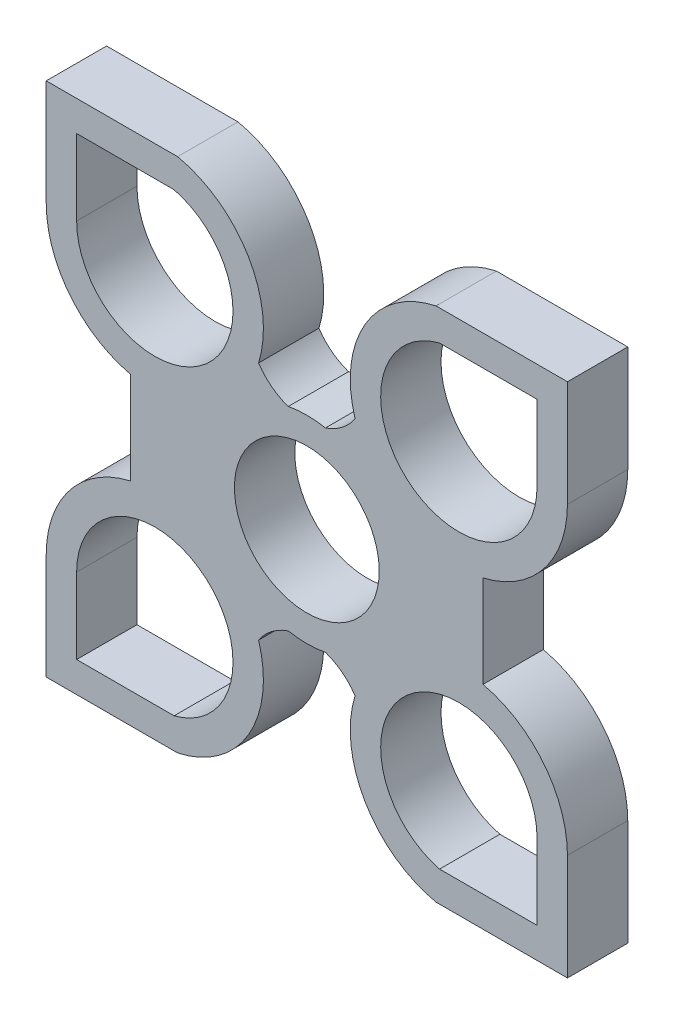
SolidWorks part; units mm, degrees
ref_plane "Front Plane" through (0, 0, 0) normal (0, 0, 1) x (1, 0, 0)
ref_plane "Top Plane" through (0, 0, 0) normal (0, 1, 0) x (1, 0, 0)
ref_plane "Right Plane" through (0, 0, 0) normal (1, 0, 0) x (0, 0, -1)
sketch "Sketch1" plane through (0, 0, 0) normal (0, 0, 1) x (1, 0, 0)
  line L1 (108, 63) -> (108, 107)
  line L2 (108, 107) -> (53.566, 107)
  line L3 (0, 107) -> (0, 0) construction
  line L4 (-95.4, -94.4) -> (-55.0125, -94.4)
  line L6 (0, 0) -> (73, 0) construction
  line L7 (73, -19.1252) -> (73, 19.1252)
  line L8 (-108, 107) -> (-53.566, 107)
  line L9 (95.4, 94.4) -> (55.0125, 94.4)
  line L10 (95.4, 63) -> (95.4, 94.4)
  line L11 (-95.4, 63) -> (-95.4, 94.4)
  line L12 (-95.4, 94.4) -> (-55.0125, 94.4)
  line L13 (-108, 63) -> (-108, 107)
  line L14 (-95.4, -63) -> (-95.4, -94.4)
  line L15 (-108, -107) -> (-53.566, -107)
  line L16 (-108, -63) -> (-108, -107)
  line L17 (95.4, -63) -> (95.4, -94.4)
  line L18 (95.4, -94.4) -> (55.0125, -94.4)
  line L19 (108, -107) -> (53.566, -107)
  line L20 (108, -63) -> (108, -107)
  line L21 (-73, -19.1252) -> (-73, 19.1252)
  circle A0 centre (0, 0) radius 30
  circle A1 centre (0, 0) radius 41
  arc A2 (53.566, 107) -> (108, 63) centre (63, 63) ccw
  arc A3 (30.5, 63) -> (95.4, 65.5475) centre (63, 63) ccw
  arc A5 (7.7032, 40.2698) -> (20, 49.7335) centre (0, 63) ccw
  arc A6 (55.0125, 94.4) -> (95.4, 63) centre (63, 63) ccw
  arc A7 (-7.7032, 40.2698) -> (-20, 49.7335) centre (0, 63) cw
  arc A8 (-53.566, 107) -> (-108, 63) centre (-63, 63) cw
  arc A9 (-30.5, 63) -> (-95.4, 65.5475) centre (-63, 63) cw
  arc A10 (-55.0125, 94.4) -> (-95.4, 63) centre (-63, 63) cw
  arc A11 (-55.0125, -94.4) -> (-95.4, -63) centre (-63, -63) ccw
  arc A12 (-53.566, -107) -> (-108, -63) centre (-63, -63) ccw
  arc A13 (7.7032, -40.2698) -> (20, -49.7335) centre (0, -63) cw
  arc A14 (-7.7032, -40.2698) -> (-20, -49.7335) centre (0, -63) ccw
  arc A15 (55.0125, -94.4) -> (95.4, -63) centre (63, -63) cw
  arc A16 (53.566, -107) -> (108, -63) centre (63, -63) cw
  dimension "D1" = 12.6
extrude "Boss-Extrude1" add sketch "Sketch1" along normal blind 25
